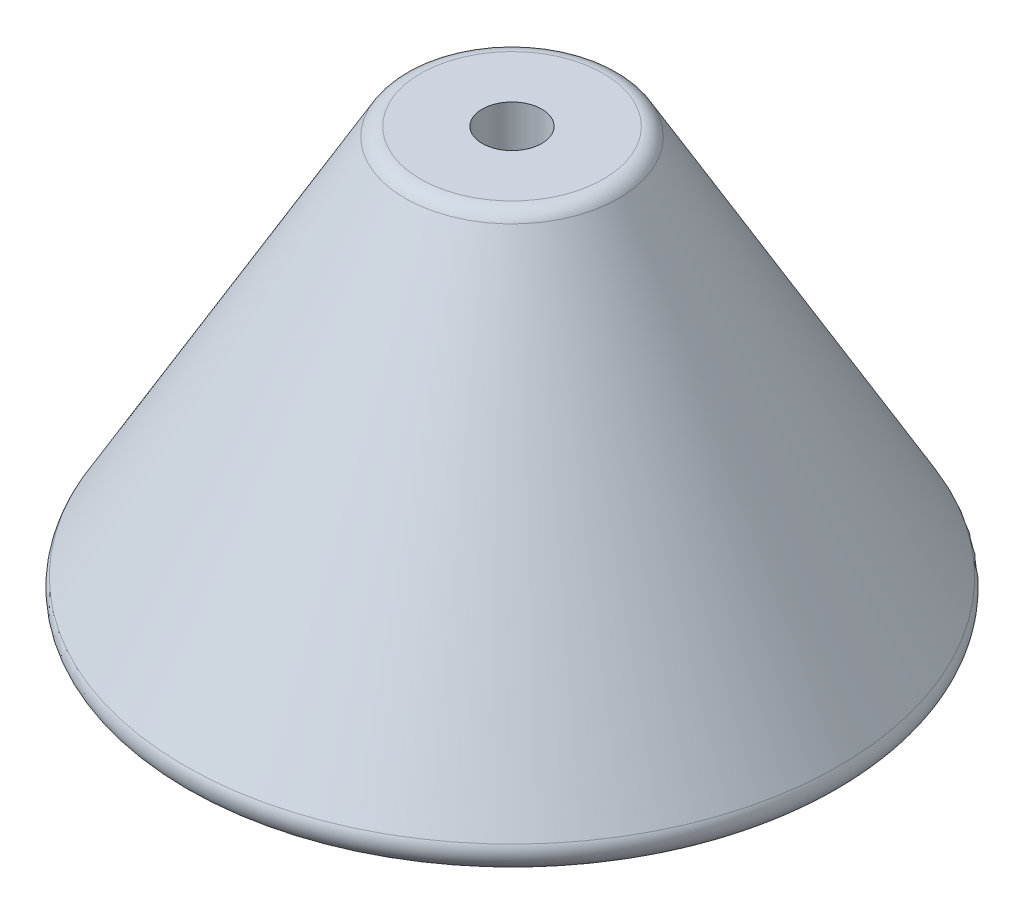
SolidWorks part; units mm, degrees
ref_plane "Front Plane" through (0, 0, 0) normal (0, 0, 1) x (1, 0, 0)
ref_plane "Top Plane" through (0, 0, 0) normal (0, 1, 0) x (1, 0, 0)
ref_plane "Right Plane" through (0, 0, 0) normal (1, 0, 0) x (0, 0, -1)
sketch "Sketch1" plane through (0, 0, 0) normal (0, 1, 0) x (1, 0, 0)
  circle A0 centre (0, 0) radius 57.5
  dimension "D1" = 115
extrude "Boss-Extrude1" add sketch "Sketch1" along normal blind 70 draft 30
sketch "Sketch3" plane through (0, 0, 0) normal (0, -1, 0) x (1, 0, 0)
  circle A0 centre (0, 0) radius 5
  dimension "D1" = 10
extrude "Cut-Extrude2" cut sketch "Sketch3" against normal through all
fillet "Fillet1" radius 3 2 edges at (0, 0, 57.5) (0, 70, 17.0855)
